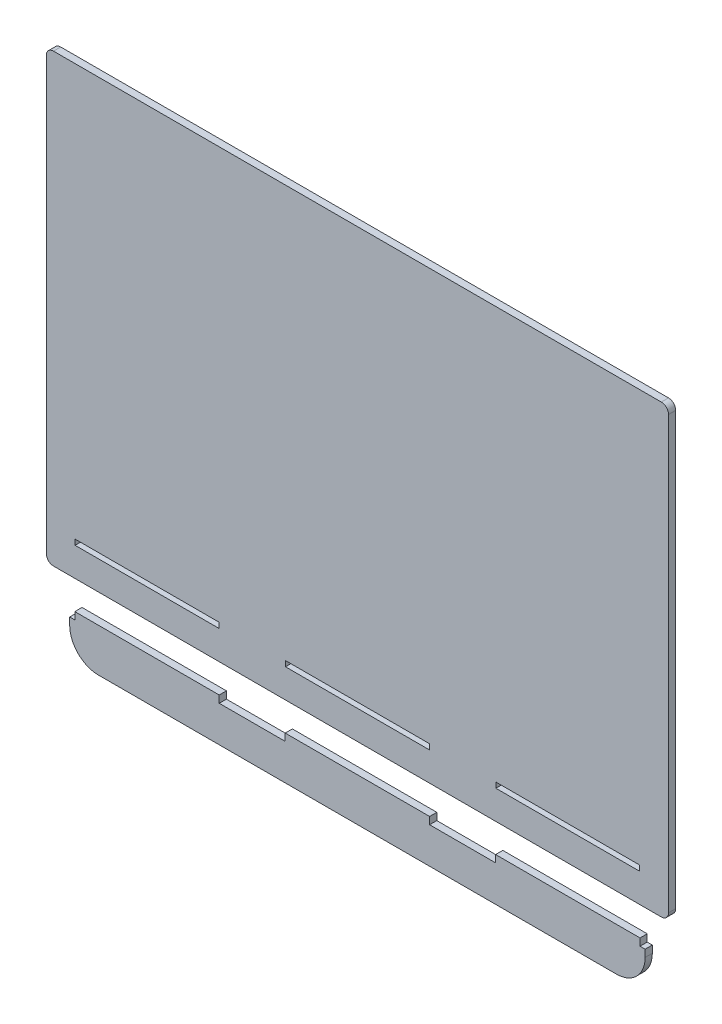
SolidWorks part; units mm, degrees
ref_plane "Front Plane" through (0, 0, 0) normal (0, 0, 1) x (1, 0, 0)
ref_plane "Top Plane" through (0, 0, 0) normal (0, 1, 0) x (1, 0, 0)
ref_plane "Right Plane" through (0, 0, 0) normal (1, 0, 0) x (0, 0, -1)
sketch "Sketch1" plane through (0, 0, 0) normal (0, 0, 1) x (1, 0, 0)
  line L1 (6.35, 0) -> (542.925, 0)
  line L2 (0, 6.35) -> (0, 387.35)
  line L3 (6.35, 393.7) -> (542.925, 393.7)
  line L4 (549.275, 6.35) -> (549.275, 387.35)
  arc A0 (6.35, 0) -> (0, 6.35) centre (6.35, 6.35) cw
  arc A1 (542.925, 0) -> (549.275, 6.35) centre (542.925, 6.35) ccw
  arc A2 (542.925, 393.7) -> (549.275, 387.35) centre (542.925, 387.35) cw
  arc A3 (0, 387.35) -> (6.35, 393.7) centre (6.35, 387.35) cw
  point P7 (0, 0)
  point P10 (549.275, 0)
  point P15 (0, 393.7)
  dimension "D3" = 6.35
  dimension "D1" = 549.275
  dimension "D2" = 393.7
extrude "Boss-Extrude1" add sketch "Sketch1" along normal blind 6.35
sketch "Sketch2" plane through (0, 0, 6.35) normal (0, 0, 1) x (1, 0, 0)
  line L0 (6.35, 0) -> (542.925, 0) construction
  line L5 (396.875, 30.1625) -> (523.875, 30.1625)
  line L6 (523.875, 30.1625) -> (523.875, 25.4)
  line L8 (274.6375, 393.7) -> (274.6375, 0) construction
  line L9 (542.925, 393.7) -> (6.35, 393.7) construction
  line L14 (211.1375, 30.1625) -> (338.1375, 30.1625)
  line L15 (211.1375, 30.1625) -> (211.1375, 25.4)
  line L16 (211.1375, 25.4) -> (338.1375, 25.4)
  line L17 (338.1375, 30.1625) -> (338.1375, 25.4)
  line L18 (211.1375, 30.1625) -> (338.1375, 25.4) construction
  line L19 (211.1375, 25.4) -> (338.1375, 30.1625) construction
  line L20 (396.875, 25.4) -> (523.875, 25.4)
  line L21 (396.875, 30.1625) -> (396.875, 25.4)
  line L22 (25.4, 30.1625) -> (152.4, 30.1625)
  line L23 (152.4, 30.1625) -> (152.4, 25.4)
  line L24 (25.4, 25.4) -> (152.4, 25.4)
  line L25 (25.4, 30.1625) -> (25.4, 25.4)
  line L26 (152.4, 25.4) -> (211.1375, 25.4) construction
  line L27 (338.1375, 25.4) -> (396.875, 25.4) construction
  line L28 (0, 387.35) -> (0, 6.35) construction
  point P21 (274.6375, 27.7813)
  dimension "D1" = 2
  dimension "D2" = 25.4
  dimension "D3" = 2
  dimension "D5" = 25.4
  dimension "D6" = 4.7625
  dimension "D7" = 127
extrude "Cut-Extrude1" cut sketch "Sketch2" against normal through all
ref_plane "Plane1" through (0, -25.4, 0) normal (0, -1, 0) x (-1, 0, 0)
sketch "Sketch3" plane through (0, -25.4, 0) normal (0, -1, 0) x (1, 0, 0)
  line L0 (0, 3.175) -> (549.275, 3.175) construction
  line L1 (0, 6.35) -> (0, 0) construction
  line L2 (549.275, 6.35) -> (549.275, 0) construction
  line L3 (274.6375, 6.35) -> (274.6375, 0) construction
  line L4 (6.35, 6.35) -> (542.925, 6.35) construction
  line L5 (6.35, 0) -> (542.925, 0) construction
  line L7 (20.6375, 0) -> (528.6375, 0)
  line L8 (20.6375, 0) -> (20.6375, 6.35)
  line L9 (20.6375, 6.35) -> (528.6375, 6.35)
  line L10 (528.6375, 0) -> (528.6375, 6.35)
  line L11 (20.6375, 0) -> (528.6375, 6.35) construction
  line L12 (20.6375, 6.35) -> (528.6375, 0) construction
  point P13 (274.6375, 3.175)
  dimension "D1" = 508
extrude "Boss-Extrude2" add sketch "Sketch3" along normal blind 38.1
sketch "Sketch8" plane through (0, 0, 6.35) normal (0, 0, 1) x (1, 0, 0)
  line L0 (-3.4925, -25.4) -> (3.4925, -25.4) construction
  line L1 (20.6375, -25.4) -> (25.146, -25.4)
  line L2 (20.6375, -25.4) -> (20.6375, -31.75)
  line L3 (20.6375, -31.75) -> (25.146, -31.75)
  line L4 (25.146, -25.4) -> (25.146, -31.75)
  line L6 (20.6375, -63.5) -> (20.6375, -25.4) construction
  line L7 (25.4, 30.1625) -> (25.4, 25.4) construction
  line L8 (152.4, 25.4) -> (152.4, 30.1625) construction
  line L9 (152.654, -25.4) -> (210.8835, -25.4)
  line L10 (152.654, -25.4) -> (152.654, -31.75)
  line L11 (152.654, -31.75) -> (210.8835, -31.75)
  line L12 (210.8835, -25.4) -> (210.8835, -31.75)
  line L13 (211.1375, 30.1625) -> (211.1375, 25.4) construction
  line L14 (274.6375, -63.5) -> (274.6375, -25.4) construction
  line L15 (528.6375, -63.5) -> (20.6375, -63.5) construction
  line L16 (338.3915, -25.4) -> (338.3915, -31.75)
  line L17 (396.621, -25.4) -> (338.3915, -25.4)
  line L18 (396.621, -31.75) -> (338.3915, -31.75)
  line L19 (396.621, -25.4) -> (396.621, -31.75)
  line L20 (528.6375, -31.75) -> (524.129, -31.75)
  line L21 (528.6375, -25.4) -> (528.6375, -31.75)
  line L22 (524.129, -25.4) -> (524.129, -31.75)
  line L23 (528.6375, -25.4) -> (524.129, -25.4)
  point P10 (25.4, 27.7812)
  dimension "D1" = 6.35
  dimension "D2" = 0.254
  dimension "D3" = 0.254
  dimension "D4" = 0.254
extrude "Cut-Extrude2" cut sketch "Sketch8" against normal through all
fillet "Fillet1" radius 25.4 2 edges at (528.6375, -63.5, 3.175) (20.6375, -63.5, 3.175)
